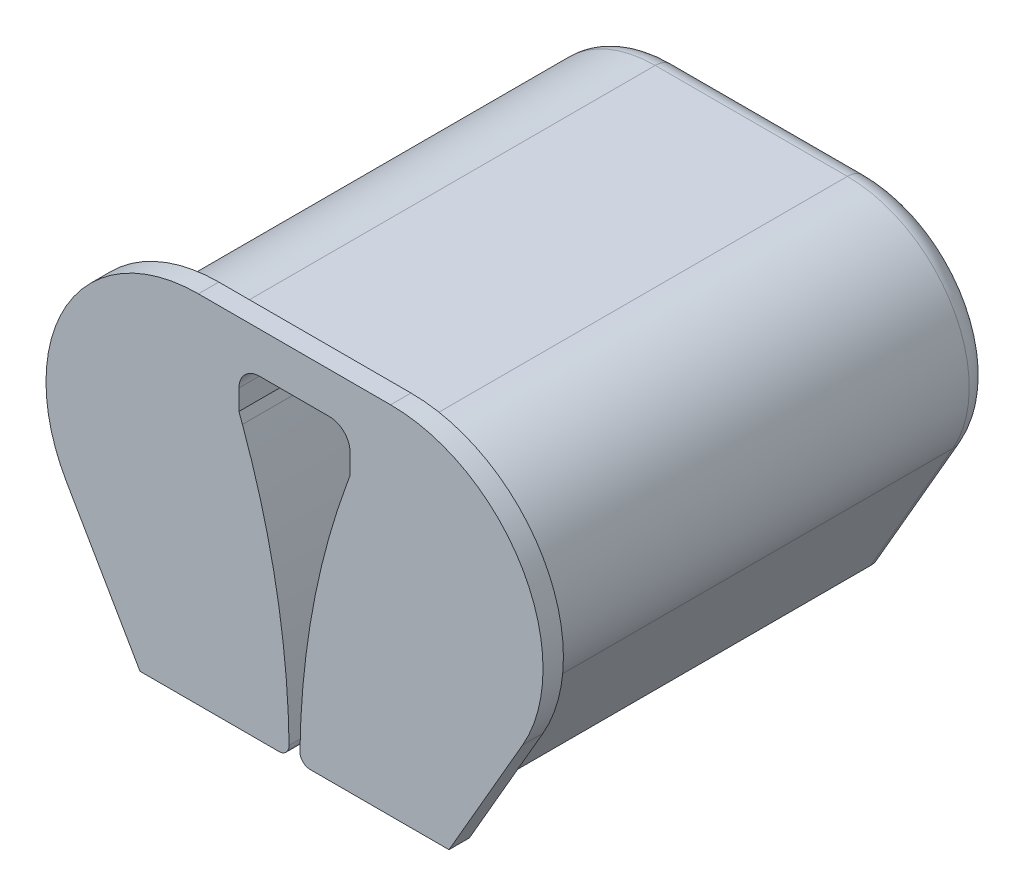
SolidWorks part; units mm, degrees
ref_plane "Front Plane" through (0, 0, 0) normal (0, 0, 1) x (1, 0, 0)
ref_plane "Top Plane" through (0, 0, 0) normal (0, 1, 0) x (1, 0, 0)
ref_plane "Right Plane" through (0, 0, 0) normal (1, 0, 0) x (0, 0, -1)
sketch "Sketch1" plane through (0, 0, 0) normal (0, 0, 1) x (1, 0, 0)
  line L0 (19.815, -18) -> (11.7321, -32) construction
  line L1 (-9.4226, 0) -> (9.4226, 0) construction
  line L2 (-11.7321, -32) -> (-19.815, -18) construction
  line L3 (19.815, -18) -> (11.7321, -32) construction
  line L4 (-9.4226, 0) -> (9.4226, 0) construction
  line L5 (-11.7321, -32) -> (-19.815, -18) construction
  line L6 (-11.6887, -31.975) -> (-19.7717, -17.975)
  line L7 (-9.4226, -0.05) -> (9.4226, -0.05)
  line L8 (19.7717, -17.975) -> (11.6887, -31.975)
  line L9 (-11.6887, -31.975) -> (11.6887, -31.975)
  arc A0 (19.815, -18) -> (9.4226, 0) centre (9.4226, -12) ccw construction
  arc A1 (-9.4226, 0) -> (-19.815, -18) centre (-9.4226, -12) ccw construction
  arc A2 (19.815, -18) -> (9.4226, 0) centre (9.4226, -12) ccw construction
  arc A3 (-9.4226, 0) -> (-19.815, -18) centre (-9.4226, -12) ccw construction
  arc A4 (-9.4226, -0.05) -> (-19.7717, -17.975) centre (-9.4226, -12) ccw
  arc A5 (19.7717, -17.975) -> (9.4226, -0.05) centre (9.4226, -12) ccw
  dimension "D1" = 0.05
extrude "Boss-Extrude1" add sketch "Sketch1" against normal offset from surface (44.9 mm away) 0.1
fillet "Fillet1" radius 2.1 5 edges at (15.7302, -24.975, -44.9) (-15.7302, -24.975, -44.9) (-19.7717, -6.025, -44.9) (0, -0.05, -44.9) (19.7717, -6.025, -44.9)
sketch "Sketch2" plane through (0, 0, 0) normal (0, 0, 1) x (1, 0, 0)
  line L0 (15.1529, -31.975) -> (22.3697, -19.475)
  line L1 (9.4226, 2.95) -> (-9.4226, 2.95)
  line L2 (-22.3697, -19.475) -> (-15.1529, -31.975)
  line L4 (-11.6887, -31.975) -> (11.6887, -31.975)
  line L5 (11.6887, -31.975) -> (19.7717, -17.975)
  line L6 (9.4226, -0.05) -> (-9.4226, -0.05)
  line L7 (-19.7717, -17.975) -> (-11.6887, -31.975)
  line L8 (-11.6887, -31.975) -> (11.6887, -31.975) construction
  line L9 (11.6887, -31.975) -> (19.7717, -17.975) construction
  line L10 (9.4226, -0.05) -> (-9.4226, -0.05) construction
  line L11 (-19.7717, -17.975) -> (-11.6887, -31.975) construction
  line L12 (-15.1529, -31.975) -> (15.1529, -31.975)
  line L13 (14.2868, -33.475) -> (22.3697, -19.475) construction
  line L14 (-22.3697, -19.475) -> (-14.2868, -33.475) construction
  arc A0 (22.3697, -19.475) -> (9.4226, 2.95) centre (9.4226, -12) ccw
  arc A1 (-9.4226, 2.95) -> (-22.3697, -19.475) centre (-9.4226, -12) ccw
  arc A2 (19.7717, -17.975) -> (9.4226, -0.05) centre (9.4226, -12) ccw
  arc A3 (-9.4226, -0.05) -> (-19.7717, -17.975) centre (-9.4226, -12) ccw
  arc A4 (19.7717, -17.975) -> (9.4226, -0.05) centre (9.4226, -12) ccw construction
  arc A5 (-9.4226, -0.05) -> (-19.7717, -17.975) centre (-9.4226, -12) ccw construction
  dimension "D1" = 0
  dimension "D2" = 3
extrude "Boss-Extrude2" add sketch "Sketch2" along normal blind 2
sketch "Sketch3" plane through (0, 0, 0) normal (0, 0, 1) x (1, 0, 0)
  line L0 (-3.4474, -1.05) -> (3.4474, -1.05)
  line L1 (5.4474, -3.05) -> (5.4474, -5.05)
  line L2 (5.4474, -5.05) -> (5.1084, -5.9815)
  line L5 (0.525, -31.975) -> (-0.525, -31.975)
  line L7 (-5.1084, -5.9815) -> (-5.4474, -5.05)
  line L8 (-5.4474, -5.05) -> (-5.4474, -3.05)
  line L9 (0, 0) -> (0, -6.5516) construction
  line L10 (-5.4474, -5.05) -> (5.4474, -5.05) construction
  line L11 (-0.525, -31.975) -> (-0.525, -5.9815) construction
  line L13 (-15.1529, -31.975) -> (15.1529, -31.975) construction
  line L14 (-0.525, -5.9815) -> (0.525, -5.9815) construction
  line L15 (0.525, -31.975) -> (0.525, -5.9815) construction
  line L18 (9.4226, -0.05) -> (-9.4226, -0.05) construction
  arc A0 (5.1084, -5.9815) -> (0.525, -31.975) centre (76.525, -31.975) ccw
  arc A1 (-0.525, -31.975) -> (-5.1084, -5.9815) centre (-76.525, -31.975) ccw
  arc A2 (3.4474, -1.05) -> (5.4474, -3.05) centre (3.4474, -3.05) cw
  arc A3 (-3.4474, -1.05) -> (-5.4474, -3.05) centre (-3.4474, -3.05) ccw
  point P11 (0, -1.05)
  point P14 (0, -31.975)
  point P26 (5.4474, -1.05)
  point P29 (-5.4474, -1.05)
  dimension "D5" = 76
  dimension "D7" = 2
  dimension "D1" = 1.05
  dimension "D2" = 1
  dimension "D3" = 4
  dimension "D4" = 20
ref_plane "Plane1" through (0, 0, -25) normal (0, 0, 1) x (1, 0, 0)
ref_plane "Plane2" through (0, 0, -25) normal (0, 0, 1) x (1, 0, 0)
extrude "Cut-Extrude1" cut sketch "Sketch3" against normal through all both and the other way through all contours L7 L8 A3 L0 A2 L1 L2 A0 L5 A1
fillet "Fillet2" radius 1 2 edges at (0.525, -31.975, -21.45) (-0.525, -31.975, -21.45)
